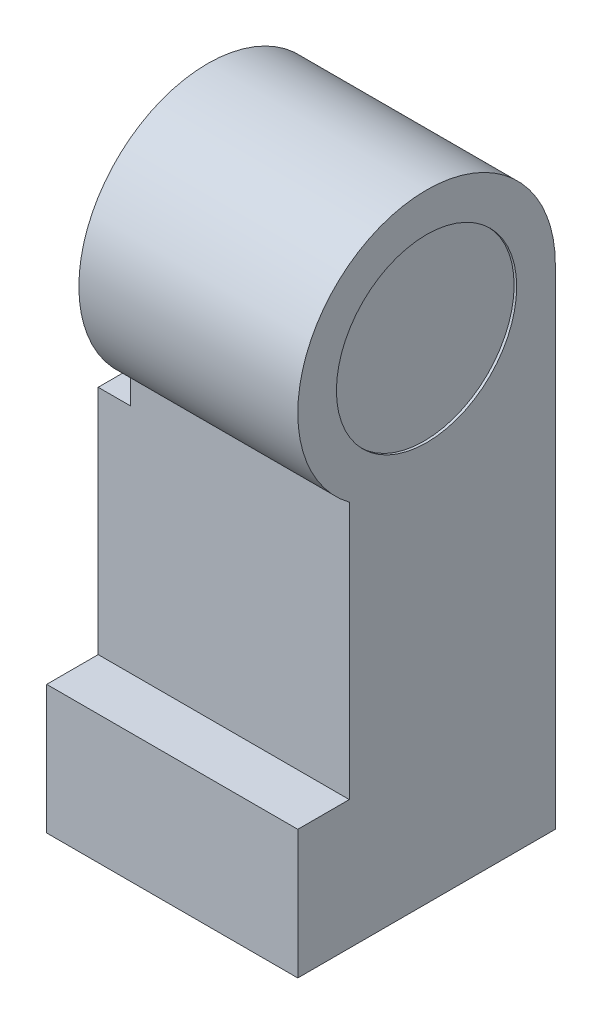
SolidWorks part; units mm, degrees
material "ABS"
ref_plane "Front Plane" through (0, 0, 0) normal (0, 0, 1) x (1, 0, 0)
ref_plane "Top Plane" through (0, 0, 0) normal (0, 1, 0) x (1, 0, 0)
ref_plane "Right Plane" through (0, 0, 0) normal (1, 0, 0) x (0, 0, -1)
sketch "Sketch1" plane through (0, 0, 0) normal (0, 1, 0) x (1, 0, 0)
  line L1 (0, -10) -> (10, -10)
  line L2 (0, -10) -> (0, 0)
  line L3 (0, 0) -> (10, 0)
  line L4 (10, -10) -> (10, 0)
  dimension "D1" = 10
  dimension "D2" = 10
extrude "Foot" add sketch "Sketch1" along normal blind 5
sketch "Sketch2" plane through (0, 5, 0) normal (0, 1, 0) x (1, 0, 0)
  line L1 (0, 0) -> (10, 0)
  line L2 (0, 0) -> (0, -8)
  line L3 (0, -8) -> (10, -8)
  line L4 (10, 0) -> (10, -8)
  line L5 (0, -10) -> (10, -10) construction
  dimension "D1" = 2
  dimension "D2" = 10
extrude "Leg" add sketch "Sketch2" along normal blind 14
sketch "Sketch3" plane through (0, 0, 0) normal (-1, 0, 0) x (0, 0, 1)
  line L2 (0, 19) -> (8, 19) construction
  circle A0 centre (5, 19) radius 5
  dimension "D1" = 5
extrude "Hip conector" add sketch "Sketch3" against normal blind 10
sketch "Sketch28" plane through (10, 0, 0) normal (1, 0, 0) x (0, 0, -1)
  circle A0 centre (-5, 19) radius 3.5
  dimension "D1" = 7
extrude "Decorative circle that makes this easy to dimension" cut sketch "Sketch28" against normal blind 0.1
sketch "Sketch19" plane through (0, 0, 0) normal (-1, 0, 0) x (0, 0, 1)
  line L0 (0, 19) -> (10, 19) construction
  line L1 (5, 13.99) -> (10, 13.99)
  line L2 (2.495, 14.6612) -> (0, 16.1017)
  line L3 (0, 19) -> (0, 0) construction
  line L4 (0, 16.1017) -> (0, 24)
  line L5 (0, 24) -> (10, 24)
  line L6 (10, 24) -> (10, 13.99)
  line L7 (2.495, 14.6612) -> (5, 19) construction
  line L8 (5, 19) -> (5, 13.99) construction
  arc A0 (8, 15) -> (0, 19) centre (5, 19) ccw construction
  arc A1 (5, 13.99) -> (2.495, 14.6612) centre (5, 19) cw
  dimension "D1" = 30
  dimension "D2" = 10.01
  dimension "D3" = 5
  dimension "D4" = 5.01
extrude "Room for hip" cut sketch "Sketch19" against normal blind 1.5
hole_wizard "Hip hole" positions "Sketch26" profile "Sketch25" hole size "Ø4.0" standard "ANSI Metric"
sketch "Sketch26" plane through (1.5, 0, 0) normal (-1, 0, 0) x (0, 0, 1)
  point P5 (5, 19)
sketch "Sketch25" plane through (1.5, 19, 5) normal (0, 1, 0) x (0, 0, 1)
  line L0 (0, 0) -> (0, 7.2017)
  line L1 (0, 7.2017) -> (2, 6)
  line L2 (2, 6) -> (2, 0)
  line L5 (2, 0) -> (0, 0)
  line L10 (0, 7.2017) -> (-2, 6) construction
  line L11 (0, -6.35) -> (0, 107.95) construction
  dimension "Hole Dia." = 4
  dimension "Hole Depth" = 6
  dimension "Drill Angle" = 118
sketch "Sketch18" plane through (0, 0, 0) normal (0, -1, 0) x (1, 0, 0)
  line L1 (2, 8) -> (8, 8)
  line L2 (2, 8) -> (2, 2)
  line L3 (2, 2) -> (8, 2)
  line L4 (8, 8) -> (8, 2)
  line L11 (10, 10) -> (10, 0) construction
  line L12 (10, 0) -> (0, 0) construction
  line L13 (0, 10) -> (10, 10) construction
  dimension "D1" = 6
  dimension "D2" = 2
  dimension "D3" = 2
  dimension "D4" = 2
extrude "Foot hole" cut sketch "Sketch18" against normal blind 2.5
hole_wizard "Weight reduction/make it easy to add centerline hole" positions "Sketch30" profile "Sketch29" hole size "Ø3.0" standard "ANSI Metric"
sketch "Sketch30" plane through (0, 2.5, 0) normal (0, -1, 0) x (-1, 0, 0)
  point P0 (-5, -5)
sketch "Sketch29" plane through (5, 2.5, 5) normal (1, 0, 0) x (0, 0, -1)
  line L0 (0, 0) -> (0, 8.9013)
  line L1 (0, 8.9013) -> (1.5, 8)
  line L2 (1.5, 8) -> (1.5, 0)
  line L5 (1.5, 0) -> (0, 0)
  line L10 (0, 8.9013) -> (-1.5, 8) construction
  line L11 (0, -6.35) -> (0, 107.95) construction
  dimension "Hole Dia." = 3
  dimension "Hole Depth" = 8
  dimension "Drill Angle" = 118
sketch "Sketch27" plane through (0, 0, 0) normal (-1, 0, 0) x (0, 0, 1)
  line L1 (10, 0) -> (0, 0)
  line L2 (10, 0) -> (10, 20)
  line L3 (10, 20) -> (0, 20)
  line L4 (0, 0) -> (0, 20)
  dimension "D1" = 20
extrude "Thigh gap" cut sketch "Sketch27" against normal blind 0.25
fillet "Smoothing edges" [suppressed] radius 0.1
scale "Scale1" scale about centroid uniform scaling yes scale factor 2
equation "\"D4@Sketch18\"=\"D2@Sketch18\""
equation "\"D3@Sketch18\"=\"D2@Sketch18\""
